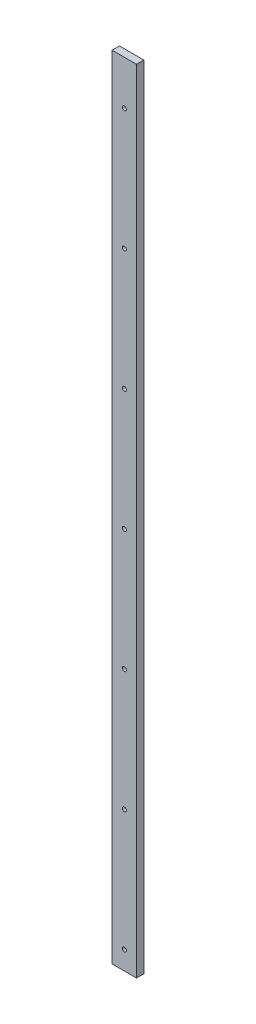
SolidWorks part; units mm, degrees
ref_plane "Front Plane" through (0, 0, 0) normal (0, 0, 1) x (1, 0, 0)
ref_plane "Top Plane" through (0, 0, 0) normal (0, 1, 0) x (1, 0, 0)
ref_plane "Right Plane" through (0, 0, 0) normal (1, 0, 0) x (0, 0, -1)
sketch "Sketch1" plane through (0, 0, 0) normal (0, 1, 0) x (1, 0, 0)
  line L1 (-20, -6) -> (20, -6)
  line L2 (-20, -6) -> (-20, 6)
  line L3 (-20, 6) -> (20, 6)
  line L4 (20, -6) -> (20, 6)
  line L5 (-20, -6) -> (20, 6) construction
  line L6 (-20, 6) -> (20, -6) construction
  point P0 (0, 0)
  dimension "D1" = 12
  dimension "D2" = 40
extrude "Boss-Extrude1" add sketch "Sketch1" against normal blind 1303.36
sketch "Sketch2" plane through (0, 0, 6) normal (0, 0, 1) x (1, 0, 0)
  line L0 (-20, -1303.36) -> (20, -1303.36) construction
  circle A0 centre (0, -1072.83) radius 3.4
  circle A1 centre (0, -872.83) radius 3.4
  circle A2 centre (0, -472.83) radius 3.4
  circle A3 centre (0, -272.83) radius 3.4
  circle A4 centre (0, -72.83) radius 3.4
  circle A5 centre (0, -672.83) radius 3.4
  circle A6 centre (0, -1272.83) radius 3.4
  dimension "D1" = 830.53
  dimension "D8" = 6.8
  dimension "D2" = 200
  dimension "D3" = 200
  dimension "D4" = 200
  dimension "D5" = 200
  dimension "D6" = 200
  dimension "D7" = 200
extrude "Cut-Extrude1" cut sketch "Sketch2" against normal through all
